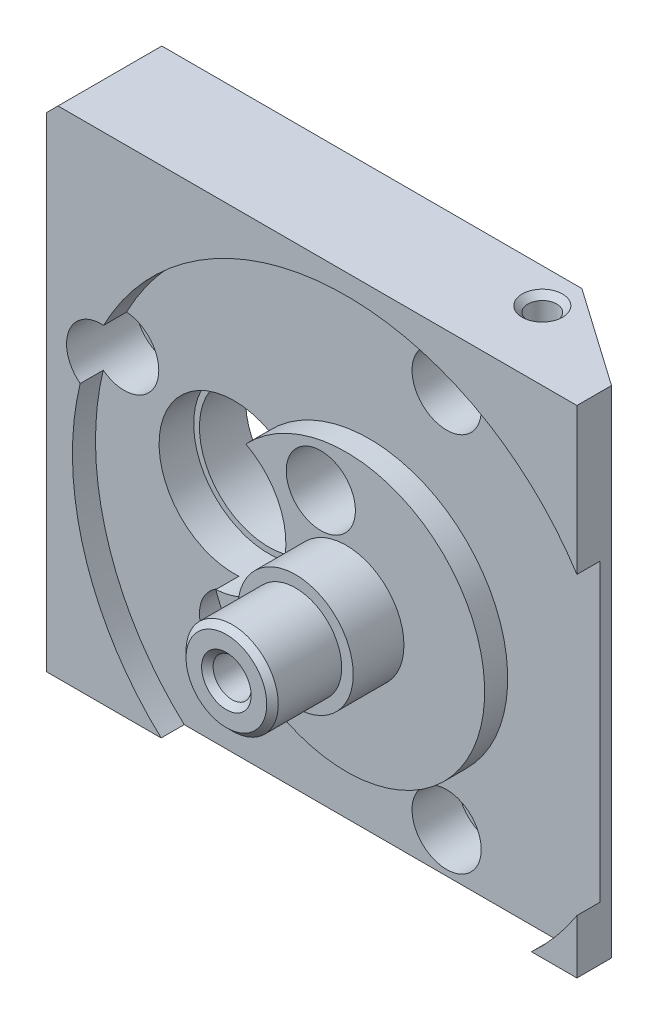
SolidWorks part; units mm, degrees
material "7075-O (SS)"
ref_plane "前视基准面" through (0, 0, 0) normal (0, 0, 1) x (1, 0, 0)
ref_plane "上视基准面" through (0, 0, 0) normal (0, 1, 0) x (1, 0, 0)
ref_plane "右视基准面" through (0, 0, 0) normal (1, 0, 0) x (0, 0, -1)
sketch "草图1" plane through (0, 0, 0) normal (0, 0, 1) x (1, 0, 0)
  line L0 (0, 22.5) -> (0, -22.5) construction
  line L1 (-26, 22.5) -> (26, 22.5)
  line L2 (-26, 22.5) -> (-26, -22.5)
  line L3 (-26, -22.5) -> (26, -22.5)
  line L4 (26, 22.5) -> (26, -22.5)
  dimension "D1" = 52
  dimension "D2" = 45
extrude "拉伸1" add sketch "草图1" along normal blind 9
sketch "草图19" plane through (0, 0, 9) normal (0, 0, 1) x (1, 0, 0)
  line L0 (26, -22.5) -> (26, 22.5) construction
  line L1 (-26, -22.5) -> (26, -22.5) construction
  circle A0 centre (0, -3) radius 12
  circle A1 centre (0, -3) radius 23.75
  dimension "D3" = 24
  dimension "D4" = 47.5
  dimension "D1" = 26
  dimension "D2" = 19.5
extrude "拉伸2" cut sketch "草图19" against normal blind 2
sketch "草图20" plane through (0, 0, 9) normal (0, 0, 1) x (1, 0, 0)
  circle A0 centre (0, -3) radius 5
  dimension "D1" = 10
extrude "拉伸3" add sketch "草图20" along normal blind 4.4
sketch "草图21" plane through (0, 0, 13.4) normal (0, 0, 1) x (1, 0, 0)
  circle A0 centre (0, -3) radius 4
  dimension "D1" = 8
extrude "拉伸4" add sketch "草图21" along normal blind 6
sketch "草图22" plane through (0, 0, 9) normal (0, 0, 1) x (1, 0, 0)
  circle A0 centre (-11.7367, -0.5) radius 6
  circle A1 centre (0, -3) radius 4 construction
  circle A2 centre (0, -3) radius 4 construction
  dimension "D3" = 12
  dimension "D1" = 2.5
  dimension "D2" = 12
extrude "拉伸5" cut sketch "草图22" against normal through all
sketch "草图23" plane through (0, 0, 9) normal (0, 0, 1) x (1, 0, 0)
  line L0 (-11.7367, -0.5) -> (-11.7367, -11.5)
  line L1 (-11.7367, -0.5) -> (-2.2104, 5)
  line L2 (-11.7367, -0.5) -> (-21.263, 5)
  circle A0 centre (-11.7367, -0.5) radius 11
  dimension "D1" = 22
  dimension "D2" = 120
  dimension "D3" = 120
hole_wizard "打孔尺寸根据内六角圆柱头螺钉的类型1" positions "3D草图2" profile "草图24" counterbore size "M3" standard "GB" end condition through all
sketch3d "3D草图2"
  point P0 (-21.263, 5, 9)
  point P3 (-11.7367, -11.5, 9)
  point P6 (-2.2104, 5, 9)
sketch "草图24" plane through (-21.263, 5, 9) normal (1, 0, 0) x (0, -1, 0)
  line L0 (0, 0) -> (0, 9)
  line L1 (0, 9) -> (1.7, 9)
  line L3 (1.7, 9) -> (1.7, 6)
  line L4 (1.7, 6) -> (3, 6)
  line L5 (3, 6) -> (3, 0)
  line L7 (3, 0) -> (0, 0)
  line L11 (0, -6.35) -> (0, 107.95) construction
  dimension "通孔孔直径" = 3.4
  dimension "通孔孔深度" = 9
  dimension "柱形沉头孔直径" = 6
  dimension "柱形沉头孔深度" = 6
sketch "草图25" plane through (0, -22.5, 0) normal (0, -1, 0) x (1, 0, 0)
  line L0 (26, 8) -> (14.5748, 0)
  line L1 (26, 9) -> (26, 0) construction
  line L2 (-26, 0) -> (26, 0) construction
  line L3 (14.5748, 0) -> (26, 0)
  line L4 (26, 0) -> (26, 8)
  dimension "D1" = 8
  dimension "D2" = 35
extrude "拉伸6" cut sketch "草图25" against normal up to surface (45 mm away) up to face at (0, 22.5, 4.5)
sketch "草图27" plane through (0, 22.5, 0) normal (0, 1, 0) x (1, 0, 0)
  line L0 (11, -3) -> (-24, -3)
  line L1 (14.5748, 0) -> (-26, 0) construction
  line L2 (26, -9) -> (26, -8) construction
  dimension "D1" = 3
  dimension "D2" = 15
  dimension "D3" = 35
hole_wizard "M3 螺纹孔1" positions "3D草图3" profile "草图28" tap size "M3" standard "GB"
sketch3d "3D草图3"
  point P3 (11, 22.5, 3)
sketch "草图28" plane through (11, 22.5, 3) normal (1, 0, 0) x (0, 0, 1)
  line L0 (0, 0) -> (0, 10.2511)
  line L1 (0, 10.2511) -> (1.25, 9.5)
  line L2 (1.25, 9.5) -> (1.25, 0)
  line L5 (1.25, 0) -> (0, 0)
  line L10 (0, 10.2511) -> (-1.25, 9.5) construction
  line L11 (0, -6.35) -> (0, 107.95) construction
  dimension "螺纹孔钻头直径" = 2.5
  dimension "螺纹孔钻头深度" = 9.5
  dimension "导头角度" = 118
cosmetic thread "孔螺蚊线5" parameters "D1"=8, "D2"=3
hole_wizard "M4 螺纹孔2" positions "3D草图4" profile "草图29" tap size "M4" standard "GB"
sketch3d "3D草图4"
  line L0 (0, -3, 19.4) -> (0, -3, 13.4) construction
  point P0 (0, -3, 19.4)
sketch "草图29" plane through (0, -3, 19.4) normal (1, 0, 0) x (0, -1, 0)
  line L0 (0, 0) -> (0, 11.0914)
  line L1 (0, 11.0914) -> (1.65, 10.1)
  line L2 (1.65, 10.1) -> (1.65, 0)
  line L5 (1.65, 0) -> (0, 0)
  line L10 (0, 11.0914) -> (-1.65, 10.1) construction
  line L11 (0, -6.35) -> (0, 107.95) construction
  dimension "螺纹孔钻头直径" = 3.3
  dimension "螺纹孔钻头深度" = 10.1
  dimension "导头角度" = 118
cosmetic thread "孔螺蚊线4" parameters "D1"=8, "D2"=4
chamfer "倒角3" distance 0.5 angle 45 2 edges at (1.65, -3, 19.4) (4, -3, 19.4)
sketch "草图30" plane through (0, -22.5, 0) normal (0, -1, 0) x (1, 0, 0)
  line L0 (11, 3) -> (-24, 3)
  line L1 (26, 9) -> (26, 8) construction
  line L2 (-26, 0) -> (14.5748, 0) construction
  line L3 (-1.2991, 0.7666) -> (-1.2991, 5.552) construction
  dimension "D1" = 35
  dimension "D2" = 15
  dimension "D3" = 3
  dimension "D4" = 12.2991
hole_wizard "M3 螺纹孔4" positions "3D草图5" profile "草图31" tap size "M3" standard "GB"
sketch3d "3D草图5"
  point P0 (11, -22.5, 3)
  point P3 (-24, -22.5, 3)
sketch "草图31" plane through (11, -22.5, 3) normal (1, 0, 0) x (0, 0, -1)
  line L0 (0, 0) -> (0, 12.2511)
  line L1 (0, 12.2511) -> (1.25, 11.5)
  line L2 (1.25, 11.5) -> (1.25, 0)
  line L5 (1.25, 0) -> (0, 0)
  line L10 (0, 12.2511) -> (-1.25, 11.5) construction
  line L11 (0, -6.35) -> (0, 107.95) construction
  dimension "螺纹孔钻头直径" = 2.5
  dimension "螺纹孔钻头深度" = 11.5
  dimension "导头角度" = 118
cosmetic thread "孔螺蚊线6" parameters "D1"=7.5, "D2"=3
cosmetic thread "孔螺蚊线7" parameters "D1"=7.5, "D2"=3
chamfer "倒角4" distance 0.5 angle 45 3 edges at (11, 22.5, 4.25) (11, -22.5, 1.75) (-24, -22.5, 1.75)
chamfer "倒角5" distance 1 angle 45 1 edges at (-26, 22.5, 4.5)
sketch "草图32" plane through (0, 0, 9) normal (0, 0, 1) x (1, 0, 0)
  line L0 (6.7, 22.5) -> (6.7, 16)
  line L1 (26, 22.5) -> (-25, 22.5) construction
  line L2 (-26, 21.5) -> (-26, -22.5) construction
  line L3 (6.7, -22.5) -> (6.7, -17)
  line L4 (-13.5577, -22.5) -> (13.5577, -22.5) construction
  dimension "D1" = 32.7
  dimension "D2" = 6.5
  dimension "D3" = 5.5
hole_wizard "打孔尺寸根据内六角圆柱头螺钉的类型2" positions "3D草图6" profile "草图33" counterbore size "M3" standard "GB" end condition through all
sketch3d "3D草图6"
  point P0 (6.7, 16, 9)
  point P3 (6.7, -17, 9)
sketch "草图33" plane through (6.7, 16, 9) normal (1, 0, 0) x (0, -1, 0)
  line L0 (0, 0) -> (0, 9)
  line L1 (0, 9) -> (1.7, 9)
  line L3 (1.7, 9) -> (1.7, 6)
  line L4 (1.7, 6) -> (3, 6)
  line L5 (3, 6) -> (3, 0)
  line L7 (3, 0) -> (0, 0)
  line L11 (0, -6.35) -> (0, 107.95) construction
  dimension "通孔孔直径" = 3.4
  dimension "通孔孔深度" = 9
  dimension "柱形沉头孔直径" = 6
  dimension "柱形沉头孔深度" = 6
sketch "Sketch1" plane through (0, 0, 7) normal (0, 0, 1) x (1, 0, 0)
  circle A0 centre (-11.7367, -0.5) radius 6.5
  dimension "D1" = 13
extrude "Extrude1" cut sketch "Sketch1" against normal blind 3 and the other way blind 6
sketch "Sketch2" plane through (0, -22.5, 0) normal (0, -1, 0) x (1, 0, 0)
  line L0 (-14, 3) -> (1, 3) construction
  line L1 (-26, 0) -> (14.5748, 0) construction
  circle A0 centre (-24, 3) radius 1.25 construction
  circle A1 centre (11, 3) radius 1.25 construction
  circle A2 centre (-14, 3) radius 1
  circle A3 centre (1, 3) radius 1
  dimension "D2" = 10
  dimension "D4" = 2
  dimension "D1" = 3
  dimension "D3" = 10
extrude "Extrude2" [suppressed] cut sketch "Sketch2" against normal blind 4.5
chamfer "Chamfer1" [suppressed] distance 0.5 angle 45
sketch "Sketch4" plane through (0, -22.5, 0) normal (0, -1, 0) x (1, 0, 0)
  line L0 (-24, 3) -> (11, 3) construction
  line L1 (-12, 7.5071) -> (-12, 0.5755) construction
  line L9 (-26, 0) -> (14.5748, 0)
  line L10 (14.5748, 0) -> (26, 8)
  line L11 (26, 8) -> (26, 9)
  line L12 (26, 9) -> (13.5577, 9)
  line L13 (13.5577, 9) -> (13.5577, 7)
  line L14 (13.5577, 7) -> (-13.5577, 7)
  line L15 (-13.5577, 7) -> (-13.5577, 9)
  line L16 (-13.5577, 9) -> (-26, 9)
  line L17 (-26, 9) -> (-26, 0)
  line L18 (-26, 0) -> (14.5748, 0)
  line L19 (14.5748, 0) -> (26, 8)
  line L20 (26, 8) -> (26, 9)
  line L21 (26, 9) -> (13.5577, 9)
  line L22 (13.5577, 9) -> (13.5577, 7)
  line L23 (13.5577, 7) -> (-13.5577, 7)
  line L24 (-13.5577, 7) -> (-13.5577, 9)
  line L25 (-13.5577, 9) -> (-26, 9)
  line L26 (-26, 9) -> (-26, 0)
  dimension "D2" = 12
  dimension "D1" = 0
extrude "Extrude3" cut sketch "Sketch4" against normal blind 2
chamfer "Chamfer2" distance 0.5 angle 45 2 edges at (11, -20.5, 1.75) (-24, -20.5, 1.75)
sketch "Sketch5" plane through (0, -20.5, 0) normal (0, -1, 0) x (1, 0, 0)
  line L0 (26, 9) -> (20, 9)
  line L1 (26, 9) -> (16.0565, 9) construction
  line L2 (20, 9) -> (20, 6)
  line L3 (20, 6) -> (11.4311, 0)
  line L4 (-26, 0) -> (14.5748, 0) construction
  line L5 (11.4311, 0) -> (14.5748, 0)
  line L6 (14.5748, 0) -> (26, 8)
  line L7 (26, 8) -> (26, 9)
  dimension "D1" = 6
  dimension "D2" = 3
extrude "Extrude4" cut sketch "Sketch5" against normal up to surface (43 mm away) up to face at (11, 22.5, 1.25)
sketch "草图34" plane through (0, -20.5, 0) normal (0, -1, 0) x (1, 0, 0)
  line L0 (-24, 3) -> (11, 3) construction
  circle A0 centre (1, 3) radius 1
  circle A1 centre (-14, 3) radius 1
  point P4 (0.4415, 3)
  dimension "D1" = 10
  dimension "D2" = 2
  dimension "D3" = 15
extrude "切除-拉伸1" cut sketch "草图34" against normal blind 4
